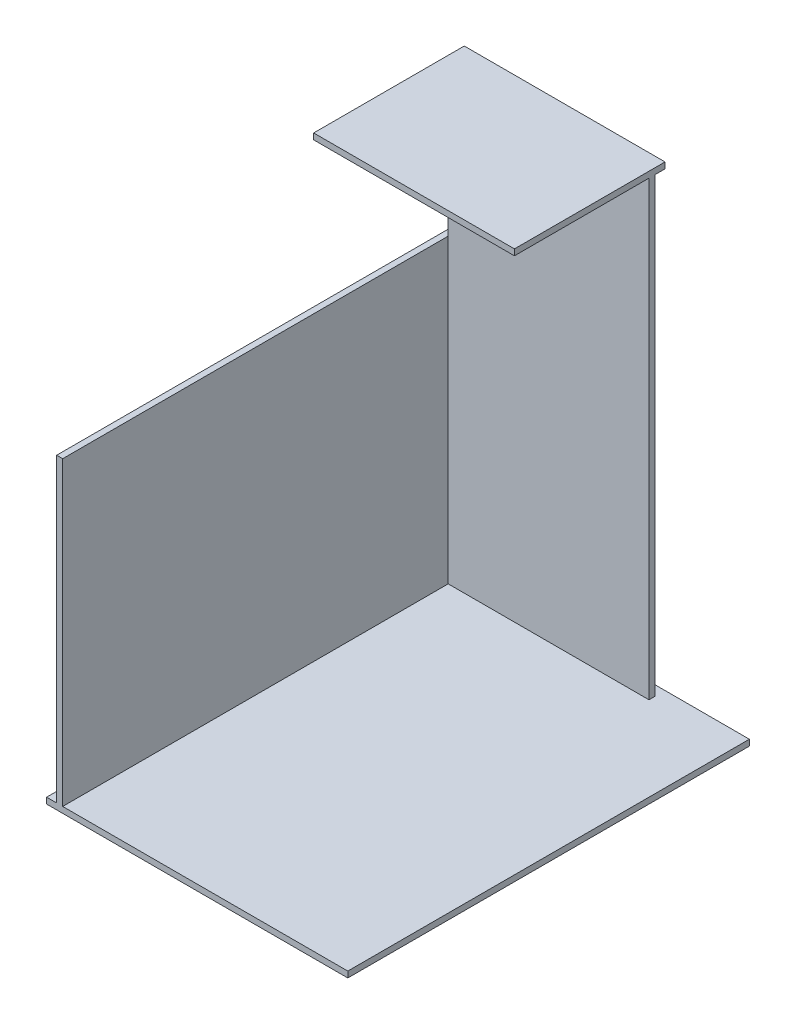
SolidWorks part; units mm, degrees
ref_plane "Front Plane" through (0, 0, 0) normal (0, 0, 1) x (1, 0, 0)
ref_plane "Top Plane" through (0, 0, 0) normal (0, 1, 0) x (1, 0, 0)
ref_plane "Right Plane" through (0, 0, 0) normal (1, 0, 0) x (0, 0, -1)
sketch "Sketch1" plane through (0, 0, 0) normal (0, 1, 0) x (1, 0, 0)
  line L1 (-150, 200) -> (150, 200)
  line L2 (-150, 200) -> (-150, -200)
  line L3 (-150, -200) -> (150, -200)
  line L4 (150, 200) -> (150, -200)
  line L5 (-150, 200) -> (150, -200) construction
  line L6 (-150, -200) -> (150, 200) construction
  point P0 (0, 0)
  dimension "D1" = 400
  dimension "D2" = 300
extrude "Boss-Extrude1" add sketch "Sketch1" along normal blind 6
sketch "Sketch2" plane through (0, 6, 0) normal (0, 1, 0) x (1, 0, 0)
  line L0 (150, 200) -> (-150, 200) construction
  line L1 (-140, 200) -> (-134, 200)
  line L2 (-140, 200) -> (-140, -200)
  line L3 (-140, -200) -> (-134, -200)
  line L4 (-134, 200) -> (-134, -200)
  line L5 (-150, -200) -> (150, -200) construction
  line L6 (-150, 200) -> (-150, -200) construction
  dimension "D1" = 10
  dimension "D2" = 6
extrude "Boss-Extrude2" add sketch "Sketch2" along normal blind 300
sketch "Sketch3" plane through (0, 6, 0) normal (0, 1, 0) x (1, 0, 0)
  line L0 (-134, -200) -> (-134, 200) construction
  line L1 (-134, 190) -> (66, 190)
  line L2 (-134, 190) -> (-134, 184)
  line L3 (-134, 184) -> (66, 184)
  line L4 (66, 190) -> (66, 184)
  line L5 (150, 200) -> (-134, 200) construction
  dimension "D1" = 10
  dimension "D2" = 6
  dimension "D3" = 200
extrude "Boss-Extrude3" add sketch "Sketch3" along normal blind 450
sketch "Sketch5" plane through (0, 456, 0) normal (0, 1, 0) x (1, 0, 0)
  line L0 (-134, -200) -> (-134, 184) construction
  line L1 (66, 200) -> (-134, 200)
  line L2 (66, 200) -> (66, 50)
  line L3 (66, 50) -> (-134, 50)
  line L4 (-134, 200) -> (-134, 50)
  line L5 (66, 184) -> (66, 190) construction
  line L6 (150, 200) -> (-134, 200) construction
  dimension "D1" = 150
extrude "Boss-Extrude4" add sketch "Sketch5" along normal blind 6
sketch "Sketch6" plane through (0, 6, 0) normal (0, 1, 0) x (1, 0, 0)
  line L0 (150, -200) -> (150, 200) construction
  line L1 (-134, -200) -> (150, -200) construction
  circle A0 centre (100, -150) radius 50
  dimension "D1" = 100
